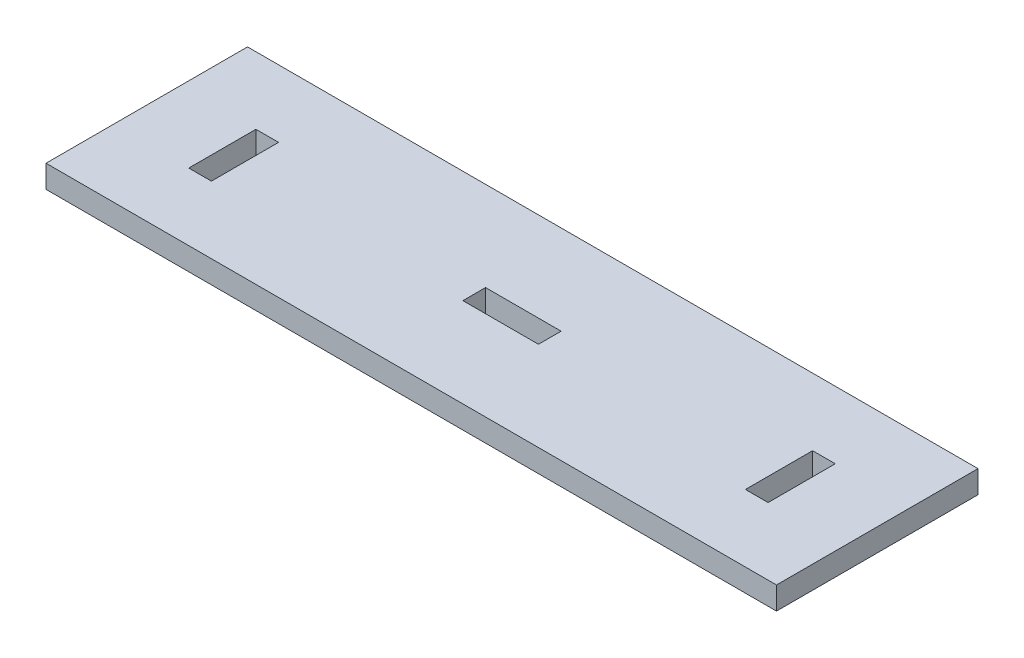
SolidWorks part; units mm, degrees
ref_plane "Front Plane" through (0, 0, 0) normal (0, 0, 1) x (1, 0, 0)
ref_plane "Top Plane" through (0, 0, 0) normal (0, 1, 0) x (1, 0, 0)
ref_plane "Right Plane" through (0, 0, 0) normal (1, 0, 0) x (0, 0, -1)
sketch "Sketch1" plane through (0, 0, 0) normal (0, 1, 0) x (1, 0, 0)
  line L0 (145, 80) -> (145, 0) construction
  line L1 (0, 0) -> (290, 0)
  line L2 (0, 0) -> (0, 80)
  line L3 (0, 80) -> (290, 80)
  line L4 (290, 0) -> (290, 80)
  line L5 (30, 53.3333) -> (39, 53.3333)
  line L6 (30, 80) -> (39, 80)
  line L7 (30, 80) -> (30, 0)
  line L8 (30, 0) -> (39, 0)
  line L9 (39, 80) -> (39, 0)
  line L10 (39, 26.6667) -> (30, 26.6667)
  line L11 (6.8547, 80) -> (6.8547, 53.3333) construction
  line L12 (6.8547, 53.3333) -> (6.8547, 26.6667) construction
  line L13 (6.8547, 26.6667) -> (6.8547, 0) construction
  line L14 (251, 26.6667) -> (260, 26.6667)
  line L15 (251, 80) -> (251, 0)
  line L16 (260, 0) -> (251, 0)
  line L17 (260, 80) -> (260, 0)
  line L18 (260, 80) -> (251, 80)
  line L19 (260, 53.3333) -> (251, 53.3333)
  line L20 (0, 40) -> (290, 40) construction
  line L21 (130, 44.5) -> (160, 44.5)
  line L22 (130, 44.5) -> (130, 35.5)
  line L23 (130, 35.5) -> (160, 35.5)
  line L24 (160, 44.5) -> (160, 35.5)
  point P33 (130, 40)
  point P34 (145, 44.5)
  dimension "D1" = 290
  dimension "D2" = 80
  dimension "D3" = 9
  dimension "D4" = 115
  dimension "D5" = 30
  dimension "9" = 9
extrude "Boss-Extrude1" add sketch "Sketch1" along normal blind 9 contours L15 L3 L9 L1 L21 L24 L23 L22 | L9 L3 L7 L5 | L9 L10 L7 L1 | L7 L3 L2 L1 | L3 L17 L1 L4 | L17 L14 L15 L1 | L19 L17 L3 L15
